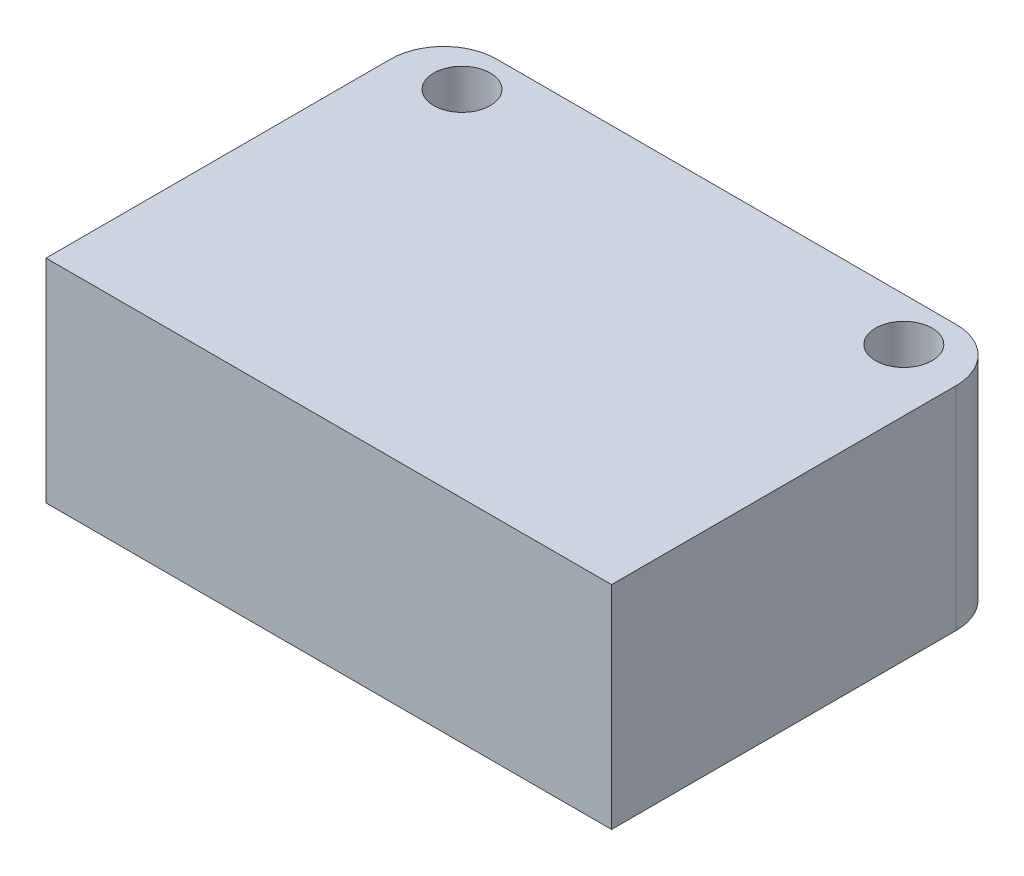
SolidWorks part; units mm, degrees
ref_plane "前视基准面" through (0, 0, 0) normal (0, 0, 1) x (1, 0, 0)
ref_plane "上视基准面" through (0, 0, 0) normal (0, 1, 0) x (1, 0, 0)
ref_plane "右视基准面" through (0, 0, 0) normal (1, 0, 0) x (0, 0, -1)
sketch "草图1" plane through (0, 0, 0) normal (0, 1, 0) x (1, 0, 0)
  line L0 (0, 0) -> (0, 21.8563) construction
  line L1 (-16, -11.25) -> (16, -11.25)
  line L2 (-16, -11.25) -> (-16, 8.25)
  line L3 (-13, 11.25) -> (13, 11.25)
  line L4 (16, -11.25) -> (16, 8.25)
  line L5 (-16, -11.25) -> (16, 11.25) construction
  line L6 (-16, 11.25) -> (16, -11.25) construction
  circle A0 centre (12.5, 8.7891) radius 1.6
  circle A1 centre (-12.5, 8.7891) radius 1.6
  arc A2 (-16, 8.25) -> (-13, 11.25) centre (-13, 8.25) cw
  arc A3 (13, 11.25) -> (16, 8.25) centre (13, 8.25) cw
  point P0 (0, 0)
  point P12 (-12.5, 10.9458)
  point P19 (-12.5, 12.75)
  point P20 (-12.5406, 12.3447)
  dimension "D4" = 3
  dimension "D5" = 3.2
  dimension "D1" = 25
  dimension "D2" = 22.5
  dimension "D3" = 32
extrude "凸台-拉伸1" add sketch "草图1" along normal mid plane 12
sketch "草图2" plane through (-16, 0, 0) normal (-1, 0, 0) x (0, 0, 1)
  line L0 (-8.25, 6) -> (-8.25, -6) construction
  circle A0 centre (-4.25, 0) radius 4
  dimension "D1" = 8
extrude "凸台-拉伸2" add sketch "草图2" along normal blind 2
fillet "圆角1" radius 1 1 edges at (-16, 0, -0.25)
